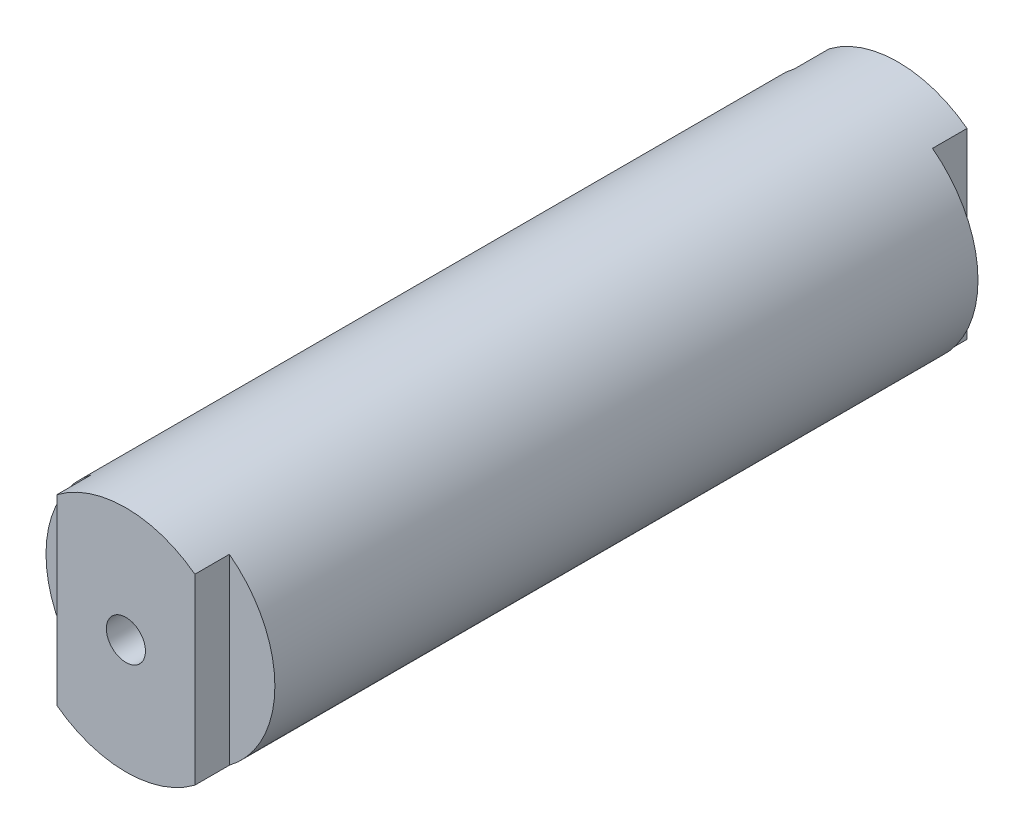
SolidWorks part; units mm, degrees
ref_plane "Front Plane" through (0, 0, 0) normal (0, 0, 1) x (1, 0, 0)
ref_plane "Top Plane" through (0, 0, 0) normal (0, 1, 0) x (1, 0, 0)
ref_plane "Right Plane" through (0, 0, 0) normal (1, 0, 0) x (0, 0, -1)
sketch "Sketch1" plane through (0, 0, 0) normal (0, 0, 1) x (1, 0, 0)
  circle A0 centre (0, 0) radius 26.3525
  dimension "D1" = 52.705
extrude "Boss-Extrude1" add sketch "Sketch1" along normal mid plane 177.8
sketch "Sketch2" plane through (0, 0, 88.9) normal (0, 0, 1) x (1, 0, 0)
  line L0 (-15.875, 21.0342) -> (-15.875, -21.0342)
  line L1 (-15.875, -21.0342) -> (15.875, -21.0342) construction
  line L2 (15.875, -21.0342) -> (15.875, 21.0342)
  arc A0 (15.875, -21.0342) -> (15.875, 21.0342) centre (0, 0) ccw
  circle A1 centre (0, 0) radius 26.3525
  arc A2 (-15.875, 21.0342) -> (-15.875, -21.0342) centre (0, 0) ccw
  dimension "D2" = 31.75
  dimension "D1" = 0
extrude "Cut-Extrude1" cut sketch "Sketch2" against normal blind 7.9502
mirror "Mirror1" about plane through (0, 0, 0) normal (0, 0, 1) of "Cut-Extrude1"
sketch "Sketch3" plane through (0, 0, 80.9498) normal (0, 0, 1) x (1, 0, 0)
  circle A0 centre (0, 0) radius 22.86
  dimension "D1" = 45.72
extrude "Cut-Extrude2" cut sketch "Sketch3" against normal offset from surface (155.8996 mm away) 3 from offset 3 up to face at (-21.1137, 0, -80.9498) offset against normal yes
sketch "Sketch5" plane through (0, 0, 88.9) normal (0, 0, 1) x (1, 0, 0)
  circle A0 centre (0, 0) radius 4.5
  dimension "D1" = 9
extrude "Cut-Extrude3" cut sketch "Sketch5" against normal through all
